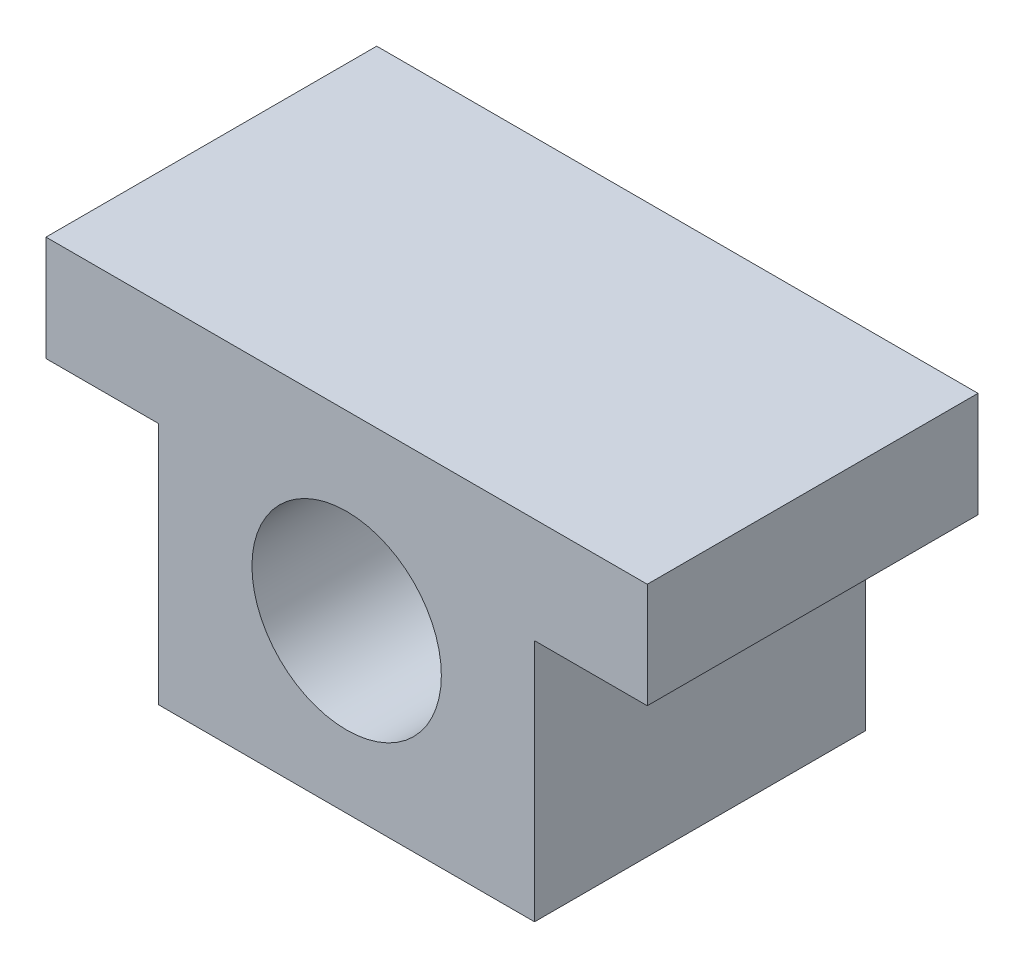
SolidWorks part; units mm, degrees
ref_plane "前视基准面" through (0, 0, 0) normal (0, 0, 1) x (1, 0, 0)
ref_plane "上视基准面" through (0, 0, 0) normal (0, 1, 0) x (1, 0, 0)
ref_plane "右视基准面" through (0, 0, 0) normal (1, 0, 0) x (0, 0, -1)
other "Configuration Table"
sketch "草图1" plane through (0, 0, 0) normal (0, 0, 1) x (1, 0, 0)
  line L0 (0, 17.5) -> (0, -43) construction
  line L1 (-100, -17.5) -> (-62.5, -17.5)
  line L2 (-100, -17.5) -> (-100, 17.5)
  line L3 (-100, 17.5) -> (100, 17.5)
  line L4 (100, -17.5) -> (100, 17.5)
  line L8 (-62.5, -17.5) -> (-62.5, -98.5)
  line L9 (-62.5, -98.5) -> (62.5, -98.5)
  line L10 (62.5, -17.5) -> (62.5, -98.5)
  line L11 (62.5, -17.5) -> (100, -17.5)
  point P0 (0, 0)
  point P13 (0, -43)
  dimension "D1" = 200
  dimension "D2" = 125
  dimension "D3" = 37.5
  dimension "D4" = 35
  dimension "D5" = 81
  dimension "D6" = 60.5
extrude "凸台-拉伸1" add sketch "草图1" along normal blind 110
sketch "草图2" plane through (0, 0, 0) normal (0, 0, -1) x (-1, 0, 0)
  line L0 (0, 17.5) -> (0, -43) construction
  line L1 (-100, 17.5) -> (100, 17.5) construction
  circle A0 centre (0, -43) radius 31.5
  dimension "D2" = 63
  dimension "D1" = 60.5
extrude "切除-拉伸1" cut sketch "草图2" against normal up to next
sketch "草图4" plane through (0, 0, 0) normal (0, 0, -1) x (-1, 0, 0)
  circle A0 centre (0, -43) radius 46.5 construction
  point P6 (32.88, -10.1191)
  dimension "D1" = 93
hole_wizard "M10 螺纹孔1" positions "草图4" profile "草图5" tap size "M10" standard "GB"
sketch "草图5" plane through (-32.88, -10.1191, 0) normal (1, 0, 0) x (0, 1, 0)
  line L0 (0, 0) -> (0, 30)
  line L1 (0, 30) -> (4.25, 27.4463)
  line L2 (4.25, 27.4463) -> (4.25, 0)
  line L5 (4.25, 0) -> (0, 0)
  line L10 (0, 30) -> (-4.25, 27.4463) construction
  line L11 (0, -6.35) -> (0, 107.95) construction
  dimension "螺纹孔钻头直径" = 8.5
  dimension "螺纹孔钻头深度" = 30
  dimension "导头角度" = 118
cosmetic thread "孔螺纹线1" parameters "D1"=20, "D2"=10
pattern_circular "阵列(圆周)1" count 4 every 30 about axis through (0, -43, 0) along (0, 0, 1) of "M10 螺纹孔1"
sketch "草图6" plane through (0, 0, 0) normal (0, 0, -1) x (-1, 0, 0)
  line L0 (0, 0) -> (0, -70.4255) construction
ref_plane "基准面1" through (0, 0, 0) normal (1, 0, 0) x (0, -1, 0)
mirror "镜向1" about plane through (0, 0, 0) normal (1, 0, 0) of "阵列(圆周)1", "M10 螺纹孔1"
